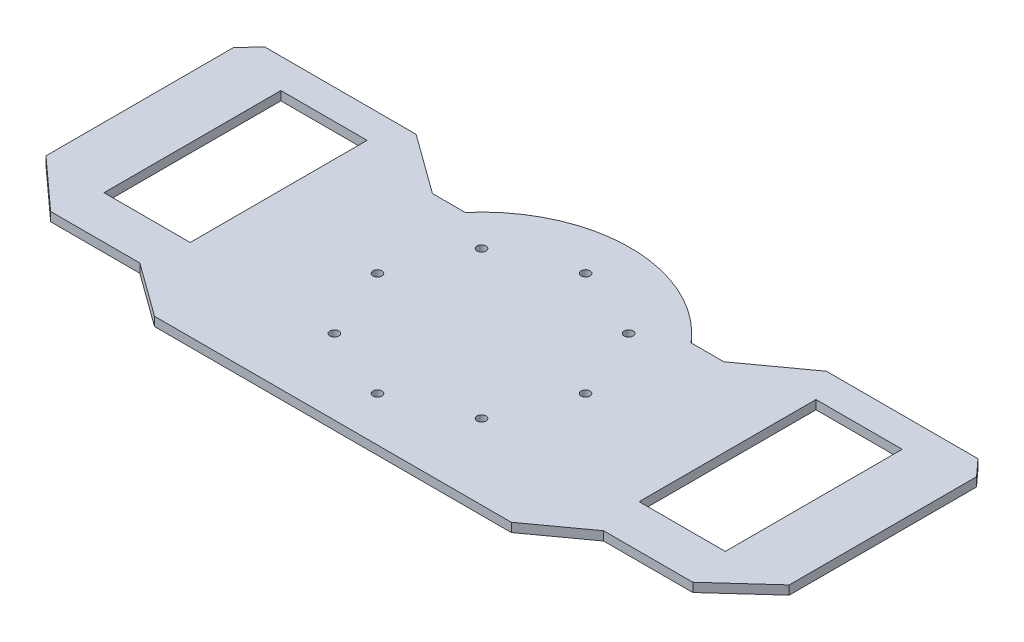
SolidWorks part; units mm, degrees
ref_plane "Front Plane" through (0, 0, 0) normal (0, 0, 1) x (1, 0, 0)
ref_plane "Top Plane" through (0, 0, 0) normal (0, 1, 0) x (1, 0, 0)
ref_plane "Right Plane" through (0, 0, 0) normal (1, 0, 0) x (0, 0, -1)
sketch "Sketch1" plane through (0, 0, 0) normal (0, 1, 0) x (1, 0, 0)
  line L4 (125, 46.4956) -> (125, -16.5044)
  line L5 (125, -16.5044) -> (108, -31.9465)
  line L6 (108, -31.9465) -> (78, -31.9465)
  line L7 (78, -31.9465) -> (60, -45)
  line L8 (60, -45) -> (-60, -45)
  line L9 (-60, -45) -> (-78, -31.9465)
  line L10 (-78, -31.9465) -> (-108, -31.9465)
  line L11 (-108, -31.9465) -> (-125, -16.5044)
  line L12 (-125, -16.5044) -> (-125, 46.4956)
  line L16 (-90, -3) -> (90, -3) construction
  line L17 (-125, 46.4956) -> (-120, 52)
  line L18 (-104.5, 42) -> (-75.5, 42)
  line L19 (-104.5, 42) -> (-104.5, -17.5)
  line L20 (-104.5, -17.5) -> (-75.5, -17.5)
  line L21 (-75.5, 42) -> (-75.5, -17.5)
  line L22 (75.5, 42) -> (104.5, 42)
  line L23 (75.5, 42) -> (75.5, -17.5)
  line L24 (75.5, -17.5) -> (104.5, -17.5)
  line L25 (104.5, 42) -> (104.5, -17.5)
  line L26 (-120, 52) -> (-69, 52)
  line L27 (-69, 52) -> (-49, 37.4962)
  line L28 (-49, 37.4962) -> (-38, 37.4962)
  line L29 (125, 46.4956) -> (120, 52)
  line L30 (120, 52) -> (69, 52)
  line L31 (69, 52) -> (49, 37.4962)
  line L32 (49, 37.4962) -> (38, 37.4962)
  circle A3 centre (-35, 5) radius 1.5
  circle A4 centre (-24.7487, -19.7487) radius 1.5
  circle A5 centre (0, -30) radius 1.5
  circle A6 centre (24.7487, -19.7487) radius 1.5
  circle A7 centre (35, 5) radius 1.5
  circle A8 centre (24.7487, 29.7487) radius 1.5
  circle A9 centre (0, 40) radius 1.5
  circle A10 centre (-24.7487, 29.7487) radius 1.5
  arc A11 (38, 37.4962) -> (-38, 37.4962) centre (0, 5) ccw
  point P23 (0, -3)
  point P34 (0, -45)
  point P51 (0, 5)
  dimension "D6" = 29
  dimension "D7" = 29
  dimension "D8" = 14.5
  dimension "D25" = 14.5
  dimension "D27" = 42
  dimension "D28" = 14.5
  dimension "D29" = 59.5
  dimension "D33" = 20
  dimension "D36" = 3
  dimension "D37" = 8
  dimension "D4" = 50
  dimension "D5" = 180
  dimension "D16" = 11
  dimension "D38" = 100
  dimension "D2" = 45
  dimension "D3" = 250
  dimension "D9" = 30
  dimension "D10" = 17
  dimension "D11" = 17
  dimension "D12" = 30
  dimension "D13" = 120
  dimension "D14" = 0
  dimension "D15" = 125
  dimension "D17" = 10
  dimension "D18" = 125
  dimension "D19" = 5
  dimension "D20" = 5
  dimension "D21" = 51
  dimension "D22" = 63
  dimension "D23" = 63
  dimension "D24" = 10
  dimension "D26" = 14.5
  dimension "D30" = 59.5
  dimension "D31" = 51
  dimension "D32" = 11
  dimension "D34" = 20
extrude "Boss-Extrude1" add sketch "Sketch1" along normal blind 3
sketch "Sketch2" plane through (0, 3, 0) normal (0, 1, 0) x (1, 0, 0)
